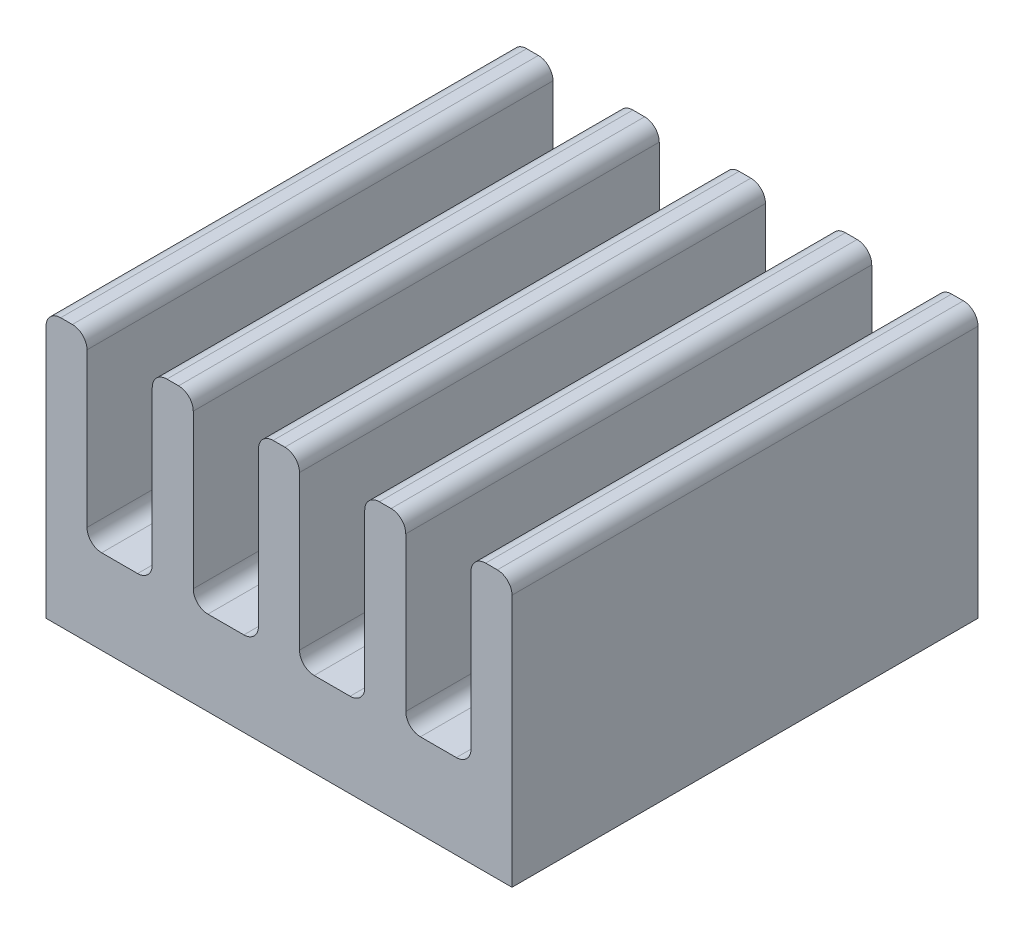
SolidWorks part; units mm, degrees
material "6061-T6 (SS)"
ref_plane "Front Plane" through (0, 0, 0) normal (0, 0, 1) x (1, 0, 0)
ref_plane "Top Plane" through (0, 0, 0) normal (0, 1, 0) x (1, 0, 0)
ref_plane "Right Plane" through (0, 0, 0) normal (1, 0, 0) x (0, 0, -1)
sketch "Sketch2" plane through (0, 0, 0) normal (0, 1, 0) x (1, 0, 0)
  line L1 (-4.445, -4.445) -> (4.445, -4.445)
  line L2 (-4.445, -4.445) -> (-4.445, 4.445)
  line L3 (-4.445, 4.445) -> (4.445, 4.445)
  line L4 (4.445, -4.445) -> (4.445, 4.445)
  line L5 (-4.445, -4.445) -> (4.445, 4.445) construction
  line L6 (-4.445, 4.445) -> (4.445, -4.445) construction
  point P0 (0, 0)
  dimension "D1" = 8.89
extrude "Boss-Extrude1" add sketch "Sketch2" along normal blind 5.1054 from offset 1.6129 offset against normal yes
sketch "Sketch3" plane through (0, 0, 0) normal (0, 1, 0) x (1, 0, 0)
  line L0 (4.445, 4.445) -> (-4.445, 4.445) construction
  line L1 (-3.6627, 4.445) -> (-2.4181, 4.445)
  line L2 (-3.6627, 4.445) -> (-3.6627, -4.445)
  line L3 (-3.6627, -4.445) -> (-2.4181, -4.445)
  line L4 (-2.4181, 4.445) -> (-2.4181, -4.445)
  line L5 (-4.445, -4.445) -> (4.445, -4.445) construction
  line L6 (-4.445, 4.445) -> (-4.445, -4.445) construction
  line L7 (4.445, -4.445) -> (4.445, 4.445) construction
  line L8 (-4.445, 4.445) -> (-4.445, -4.445)
  line L9 (-4.445, -4.445) -> (4.445, -4.445)
  line L10 (4.445, -4.445) -> (4.445, 4.445)
  line L11 (4.445, 4.445) -> (-4.445, 4.445)
  line L12 (-0.3912, 4.445) -> (-0.3912, -4.445)
  line L13 (-1.6358, 4.445) -> (-1.6358, -4.445)
  line L14 (-1.6358, 4.445) -> (-0.3912, 4.445)
  line L15 (-1.6358, -4.445) -> (-0.3912, -4.445)
  line L16 (1.6358, 4.445) -> (1.6358, -4.445)
  line L17 (0.3912, 4.445) -> (0.3912, -4.445)
  line L18 (0.3912, 4.445) -> (1.6358, 4.445)
  line L19 (0.3912, -4.445) -> (1.6358, -4.445)
  line L20 (3.6627, 4.445) -> (3.6627, -4.445)
  line L21 (2.4181, 4.445) -> (2.4181, -4.445)
  line L22 (2.4181, 4.445) -> (3.6627, 4.445)
  line L23 (2.4181, -4.445) -> (3.6627, -4.445)
  line L24 (-4.445, -4.445) -> (-4.445, -5.0787) construction
  line L25 (-4.445, -5.0787) -> (-3.6627, -5.0787) construction
  line L26 (-3.6627, -5.0787) -> (-2.4181, -5.0787) construction
  line L27 (-2.4181, -5.0787) -> (-1.6358, -5.0787) construction
  line L28 (-1.6358, -5.0787) -> (-0.3912, -5.0787) construction
  line L29 (-0.3912, -5.0787) -> (0.3912, -5.0787) construction
  line L30 (0.3912, -5.0787) -> (1.6358, -5.0787) construction
  line L31 (1.6358, -5.0787) -> (2.4181, -5.0787) construction
  line L32 (2.4181, -5.0787) -> (3.6627, -5.0787) construction
  line L33 (3.6627, -5.0787) -> (4.445, -5.0787) construction
  line L34 (4.445, -5.0787) -> (4.445, -4.5716) construction
  line L35 (3.6627, -4.445) -> (3.6627, -5.0787) construction
  line L36 (2.4181, -4.445) -> (2.4181, -5.0787) construction
  line L37 (1.6358, -4.445) -> (1.6358, -5.0787) construction
  line L38 (0.3912, -4.445) -> (0.3912, -5.0787) construction
  line L39 (-0.3912, -4.445) -> (-0.3912, -5.0787) construction
  line L40 (-1.6358, -4.445) -> (-1.6358, -5.0787) construction
  line L41 (-2.4181, -4.445) -> (-2.4181, -5.0787) construction
  line L42 (-3.6627, -4.445) -> (-3.6627, -5.0787) construction
  dimension "D2" = 1.2446
  dimension "D3" = 4
extrude "Cut-Extrude1" cut sketch "Sketch3" along normal through all contours L4 L1 L2 L3 | L11 L13 L9 L12 | L11 L17 L9 L16 | L11 L21 L9 L20
fillet "Fillet1" radius 0.2794 18 edges at (-0.3912, 0, 0) (3.6627, 0, 0) (1.6358, 0, 0) (2.4181, 0, 0) (0.3912, 0, 0) (-1.6358, 0, 0) (-3.6627, 0, 0) (-2.4181, 0, 0) (-4.445, 3.4925, 0) (-3.6627, 3.4925, 0) (-2.4181, 3.4925, 0) (-1.6358, 3.4925, 0) (-0.3912, 3.4925, 0) (0.3912, 3.4925, 0) (1.6358, 3.4925, 0) (2.4181, 3.4925, 0) (3.6627, 3.4925, 0) (4.445, 3.4925, 0)
